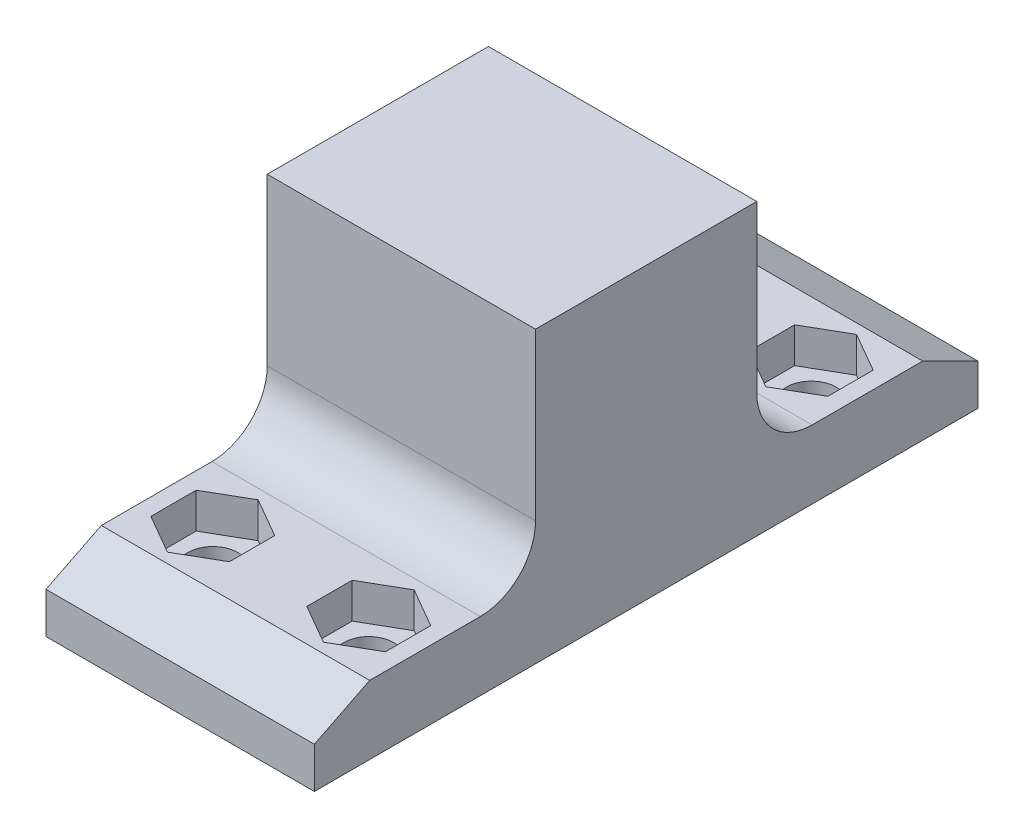
SolidWorks part; units mm, degrees
ref_plane "Спереди" through (0, 0, 0) normal (0, 0, 1) x (1, 0, 0)
ref_plane "Сверху" through (0, 0, 0) normal (0, 1, 0) x (1, 0, 0)
ref_plane "Справа" through (0, 0, 0) normal (1, 0, 0) x (0, 0, -1)
sketch "Эскиз1" plane through (0, 0, 0) normal (0, 0, 1) x (1, 0, 0)
  line L1 (0, 0) -> (24.26, 0)
  line L2 (0, 0) -> (0, 6.2)
  line L3 (0, 6.2) -> (24.26, 6.2)
  line L4 (24.26, 0) -> (24.26, 6.2)
  dimension "D1" = 6.2
  dimension "D2" = 24.26
extrude "Бобышка-Вытянуть1" add sketch "Эскиз1" along normal blind 60
sketch "Эскиз2" plane through (0, 6.2, 0) normal (0, 1, 0) x (1, 0, 0)
  line L0 (24.26, 0) -> (0, 0) construction
  line L1 (24.26, -60) -> (0, -60) construction
  line L2 (5.08, -50) -> (19.18, -50) construction
  line L3 (12.13, -50) -> (12.13, -60) construction
  line L5 (5.08, -14.0992) -> (8.63, -12.0496)
  line L6 (8.63, -12.0496) -> (8.63, -7.9504)
  line L7 (8.63, -7.9504) -> (5.08, -5.9008)
  line L8 (5.08, -5.9008) -> (1.53, -7.9504)
  line L9 (1.53, -7.9504) -> (1.53, -12.0496)
  line L10 (1.53, -12.0496) -> (5.08, -14.0992)
  line L11 (19.18, -14.0992) -> (22.73, -12.0496)
  line L12 (22.73, -12.0496) -> (22.73, -7.9504)
  line L13 (22.73, -7.9504) -> (19.18, -5.9008)
  line L14 (19.18, -5.9008) -> (15.63, -7.9504)
  line L15 (15.63, -7.9504) -> (15.63, -12.0496)
  line L16 (15.63, -12.0496) -> (19.18, -14.0992)
  line L17 (5.08, -54.0992) -> (8.63, -52.0496)
  line L18 (8.63, -52.0496) -> (8.63, -47.9504)
  line L19 (8.63, -47.9504) -> (5.08, -45.9008)
  line L20 (5.08, -45.9008) -> (1.53, -47.9504)
  line L21 (1.53, -47.9504) -> (1.53, -52.0496)
  line L22 (1.53, -52.0496) -> (5.08, -54.0992)
  line L23 (19.18, -54.0992) -> (22.73, -52.0496)
  line L24 (22.73, -52.0496) -> (22.73, -47.9504)
  line L25 (22.73, -47.9504) -> (19.18, -45.9008)
  line L26 (19.18, -45.9008) -> (15.63, -47.9504)
  line L27 (15.63, -47.9504) -> (15.63, -52.0496)
  line L28 (15.63, -52.0496) -> (19.18, -54.0992)
  circle A0 centre (5.08, -10) radius 3.55 construction
  circle A1 centre (19.18, -10) radius 3.55 construction
  circle A2 centre (5.08, -50) radius 3.55 construction
  circle A3 centre (19.18, -50) radius 3.55 construction
  point P0 (5.08, -10)
  point P1 (19.18, -10)
  point P2 (19.18, -50)
  point P3 (5.08, -50)
  dimension "D1" = 10
  dimension "D2" = 10
  dimension "D3" = 14.1
  dimension "D4" = 7.1
extrude "Вырез-Вытянуть1" cut sketch "Эскиз2" against normal blind 3.2 contours L21 L22 L17 L18 L19 L20 | L27 L28 L23 L24 L25 L26 | L15 L16 L11 L12 L13 L14 | L5 L6 L7 L8 L9 L10
sketch "Эскиз4" plane through (0, 3, 0) normal (0, 1, 0) x (1, 0, 0)
  line L0 (1.53, -7.9504) -> (1.53, -12.0496) construction
  line L1 (1.53, -47.9504) -> (1.53, -52.0496) construction
  point P0 (5.08, -50)
  point P1 (19.18, -50)
  point P2 (19.18, -10)
  point P3 (5.08, -10)
  point P4 (0, 0)
  point P8 (1.53, -10)
  point P15 (1.53, -50)
hole_wizard "Отверстие с зазором M41" positions "Трехмерный эскиз1" profile "Эскиз5" hole size "M4" standard "Ansi Metric" end condition through all
sketch3d "Трехмерный эскиз1"
  point P0 (5.08, 3, 50)
  point P3 (19.18, 3, 50)
  point P6 (5.08, 3, 10)
  point P9 (19.18, 3, 10)
sketch "Эскиз5" plane through (5.08, 3, 50) normal (1, 0, 0) x (0, 0, 1)
  line L0 (0, 0) -> (0, 3)
  line L1 (0, 3) -> (2.25, 3)
  line L2 (2.25, 3) -> (2.25, 0)
  line L5 (2.25, 0) -> (0, 0)
  line L11 (0, -6.35) -> (0, 107.95) construction
  dimension "Диаметр сквозного отверстия" = 4.5
  dimension "Глубина сквозного отверстия" = 3
sketch "Эскиз6" plane through (0, 0, 0) normal (-1, 0, 0) x (0, 0, 1)
  line L0 (20, 26.2) -> (40, 26.2)
  line L1 (40, 26.2) -> (40, 11.2)
  line L3 (20, 26.2) -> (20, 11.2)
  line L4 (60, 6.2) -> (0, 6.2) construction
  line L5 (45, 6.2) -> (15, 6.2)
  line L6 (15, 6.2) -> (14.9573, 5.9845)
  line L7 (30, 26.2) -> (30, 6.2) construction
  line L8 (30, 6.2) -> (0, 6.2) construction
  line L9 (30, 6.2) -> (60, 6.2) construction
  arc A0 (15, 6.2) -> (20, 11.2) centre (15, 11.2) ccw
  arc A1 (45, 6.2) -> (40, 11.2) centre (45, 11.2) cw
  line M11 (60, 6.2) -> (0, 6.2)
  dimension "D1" = 5
  dimension "D2" = 5
  dimension "D5" = 30
  dimension "D3" = 20
  dimension "D4" = 20
extrude "Бобышка-Вытянуть2" add sketch "Эскиз6" against normal up to surface (24.26 mm away) contours A1 L1 L0 L3 A0 M11 up to face at (24.26, 3.1, 30)
chamfer "Фаска1" distance 2.5 distance2 5 1 edges at (12.13, 6.2, 0)
chamfer "Фаска2" distance 5 distance2 2.5 1 edges at (12.13, 6.2, 60)
ref_plane "Плоскость1" through (8.63, 6.2, 47.9504) normal (0, 1, 0) x (1, 0, 0)
